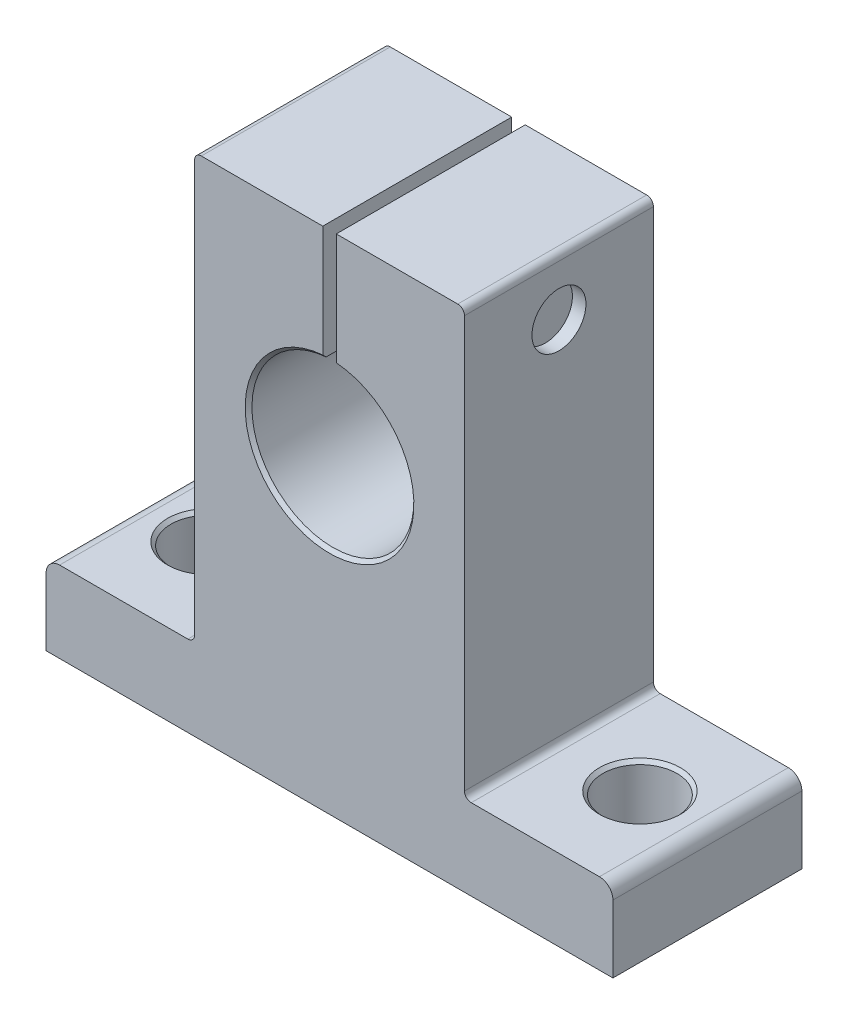
SolidWorks part; units mm, degrees
ref_plane "Front Plane" through (0, 0, 0) normal (0, 0, 1) x (1, 0, 0)
ref_plane "Top Plane" through (0, 0, 0) normal (0, 1, 0) x (1, 0, 0)
ref_plane "Right Plane" through (0, 0, 0) normal (1, 0, 0) x (0, 0, -1)
sketch "Sketch1" plane through (0, 0, 0) normal (0, 0, 1) x (1, 0, 0)
  line L0 (-21, 0) -> (21, 0)
  line L1 (-21, 0) -> (-21, 6)
  line L2 (-21, 6) -> (-10, 6)
  line L3 (-10, 6) -> (-10, 37.5)
  line L4 (-10, 37.5) -> (-0.5, 37.5)
  line L5 (10, 37.5) -> (10, 6)
  line L6 (10, 6) -> (21, 6)
  line L7 (21, 6) -> (21, 0)
  line L8 (-0.5, 37.5) -> (-0.5, 28.9791)
  line L9 (0.5, 37.5) -> (0.5, 28.9791)
  line L10 (0.5, 37.5) -> (10, 37.5)
  arc A0 (-0.5, 28.9791) -> (0.5, 28.9791) centre (0, 23) ccw
  point P11 (0, 0)
  point P13 (-0.5, 33.2396)
  dimension "D6" = 6
  dimension "D1" = 42
  dimension "D2" = 6
  dimension "D3" = 23
  dimension "D4" = 37.5
  dimension "D5" = 1
  dimension "D7" = 20
extrude "Boss-Extrude1" add sketch "Sketch1" along normal blind 14
sketch "Sketch3" plane through (0, 0, 0) normal (0, -1, 0) x (1, 0, 0)
  line L0 (-16, 7) -> (16, 7) construction
  line L1 (-21, 14) -> (-21, 0) construction
  line L2 (0, 7) -> (0, 0) construction
  circle A0 centre (-16, 7) radius 2.75
  circle A1 centre (16, 7) radius 2.75
  point P7 (-21, 7)
  dimension "D2" = 5.5
  dimension "D1" = 32
extrude "Cut-Extrude1" cut sketch "Sketch3" against normal blind 6 and the other way through all
fillet "Fillet1" radius 1 2 edges at (21, 6, 7) (-21, 6, 7)
fillet "Fillet2" radius 0.5 4 edges at (-10, 37.5, 7) (10, 37.5, 7) (10, 6, 7) (-10, 6, 7)
chamfer "Chamfer1" distance 0.25 6 edges at (-16, 0, 9.75) (16, 0, 9.75) (18.75, 6, 7) (-13.25, 6, 7) (0, 17, 0) (0, 17, 14)
sketch "Sketch4" plane through (-10, 0, 0) normal (-1, 0, 0) x (0, 0, 1)
  line L0 (14, 37) -> (0, 37) construction
  line L1 (0, 37.5) -> (14, 37.5) construction
  circle A0 centre (7, 33.25) radius 3.1
  point P6 (7, 37)
  dimension "D1" = 6.2
  dimension "D2" = 4.25
extrude "Cut-Extrude2" cut sketch "Sketch4" against normal blind 1
sketch "Sketch5" plane through (-9, 0, 0) normal (-1, 0, 0) x (0, 0, 1)
  circle A0 centre (7, 33.25) radius 3.1
  circle A1 centre (7, 33.25) radius 3
  dimension "D1" = 6
  dimension "D2" = 6.2
extrude "Cut-Extrude3" cut sketch "Sketch5" against normal blind 4
chamfer "Chamfer2" distance 0.2 1 edges at (-9, 30.25, 7)
sketch "Sketch6" plane through (-9, 0, 0) normal (-1, 0, 0) x (0, 0, 1)
  line L1 (7.2461, 31.5355) -> (8.6078, 32.6059)
  line L2 (8.6078, 32.6059) -> (8.3618, 34.3203)
  line L3 (8.3618, 34.3203) -> (6.7539, 34.9645)
  line L4 (6.7539, 34.9645) -> (5.3922, 33.8941)
  line L5 (5.3922, 33.8941) -> (5.6382, 32.1797)
  line L6 (5.6382, 32.1797) -> (7.2461, 31.5355)
  circle A0 centre (7, 33.25) radius 1.5 construction
  dimension "D1" = 3
extrude "Cut-Extrude4" cut sketch "Sketch6" against normal blind 2
sketch "Sketch7" plane through (-0.5, 0, 0) normal (1, 0, 0) x (0, 0, -1)
  circle A0 centre (-7, 33.25) radius 2
  dimension "D1" = 4
extrude "Boss-Extrude2" add sketch "Sketch7" along normal blind 1
sketch "Sketch8" plane through (10, 0, 0) normal (1, 0, 0) x (0, 0, -1)
  circle A0 centre (-7, 33.25) radius 2
  dimension "D1" = 4
extrude "Cut-Extrude5" cut sketch "Sketch8" against normal blind 1
sketch "Sketch9" plane through (-9, 0, 0) normal (-1, 0, 0) x (0, 0, 1)
  circle A0 centre (7, 33.25) radius 1.7321
extrude "Cut-Extrude6" cut sketch "Sketch9" against normal blind 1 draft 45
equation "\"h\"= 23'6"
equation "\"w\"= 42'1"
equation "\"l\"= 14'3"
equation "\"f\"= 37.5'2"
equation "\"g\"= 6'9"
equation "\"p\"= 20'5"
equation "\"b\"= 32'4"
equation "\"s\"= 5.5'10"
equation "\"sk\"= 12'7 dg kinh truc"
equation "\"D1@Sketch1\"=\"w\""
equation "\"D2@Sketch1\"=\"g\""
equation "\"D3@Sketch1\"=\"h\""
equation "\"D4@Sketch1\"=\"f\""
equation "\"rk\"= 1'11 be rong khe"
equation "\"D5@Sketch1\"=\"rk\""
equation "\"D6@Sketch1\"=\"sk\"/2"
equation "\"D1@Boss-Extrude1\"=\"l\""
equation "\"D1@Sketch3\"=\"b\""
equation "\"D2@Sketch3\"=\"s\""
equation "\"D1@Cut-Extrude1\"=\"g\""
equation "\"D7@Sketch1\"=\"p\""
equation "\"bo\"= 1'12 bo goc"
equation "\"D1@Fillet1\"=\"bo\""
equation "\"D1@Fillet2\"=\"bo\"/2"
equation "\"D1@Chamfer1\"=\"bo\"/4"
equation "\"m\"= 4'8 bu long"
equation "\"D1@Sketch4\"=1.5*\"m\"+0.2"
equation "\"D1@Sketch5\"=\"m\"*1.5"
equation "\"D2@Sketch5\"=\"m\"*1.5+0.2"
equation "\"D1@Cut-Extrude3\"=\"m\""
equation "\"D1@Chamfer2\"=\"m\"*0.05"
equation "\"D1@Cut-Extrude4\"=\"m\"/2"
equation "\"D1@Sketch6\"=\"m\"*3/4"
equation "\"D1@Sketch7\"=\"m\""
equation "\"D1@Boss-Extrude2\"=\"rk\""
equation "\"D1@Sketch8\"=\"m\""
equation "\"D2@Sketch4\"=(\"f\"-\"h\"-\"sk\"/2)/2"
